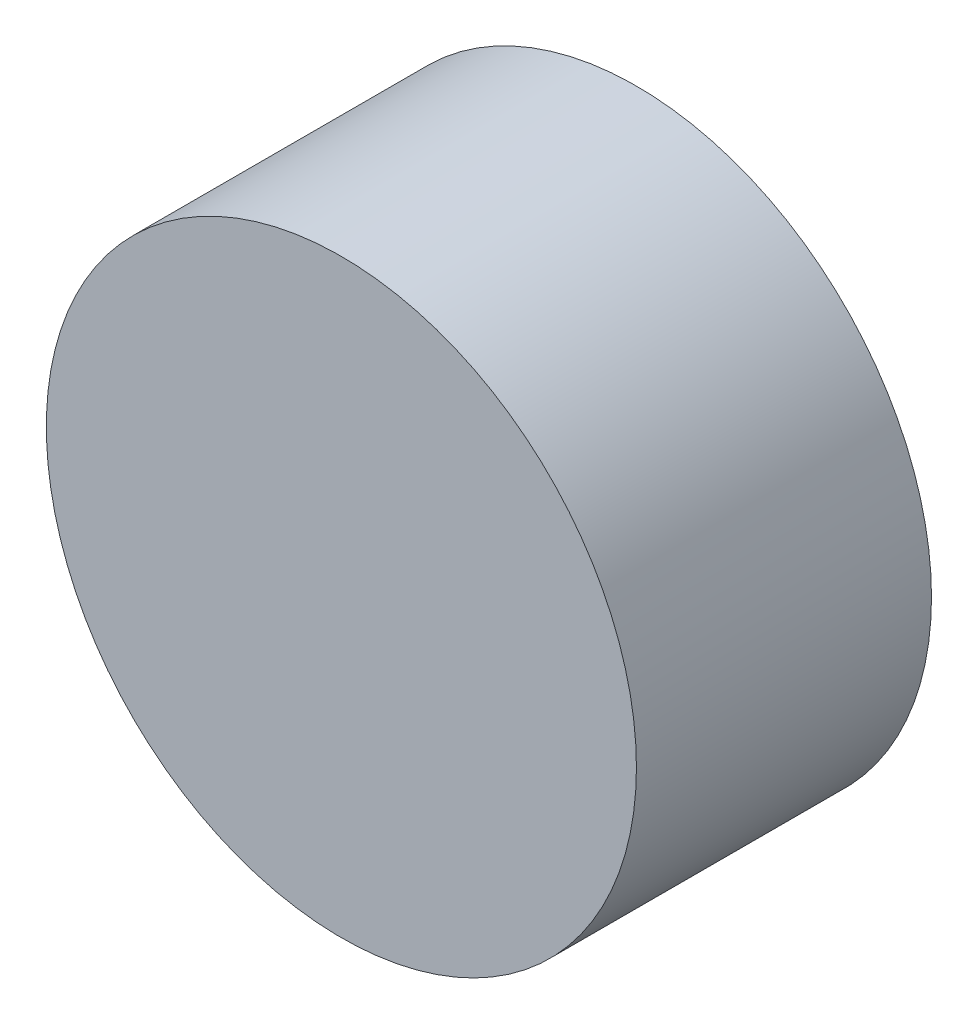
SolidWorks part; units mm, degrees
ref_plane "Front Plane" through (0, 0, 0) normal (0, 0, 1) x (1, 0, 0)
ref_plane "Top Plane" through (0, 0, 0) normal (0, 1, 0) x (1, 0, 0)
ref_plane "Right Plane" through (0, 0, 0) normal (1, 0, 0) x (0, 0, -1)
sketch "Sketch1" plane through (0, 0, 0) normal (0, 0, 1) x (1, 0, 0)
  circle A0 centre (7, 7) radius 7
  dimension "D1" = 14
extrude "Profile" add sketch "Sketch1" along normal blind 7
equation "\"Profile_Depth\" = 7mm"
equation "\"D1@Profile\" = \"Profile_Depth\""
equation "\"Profile_Sketch_1\" = 14mm"
equation "\"D1@Sketch1\" = \"Profile_Sketch_1\""
equation "\"EnvelopeWidth\" = 14mm"
equation "\"EnvelopeHeight\" = 14mm"
